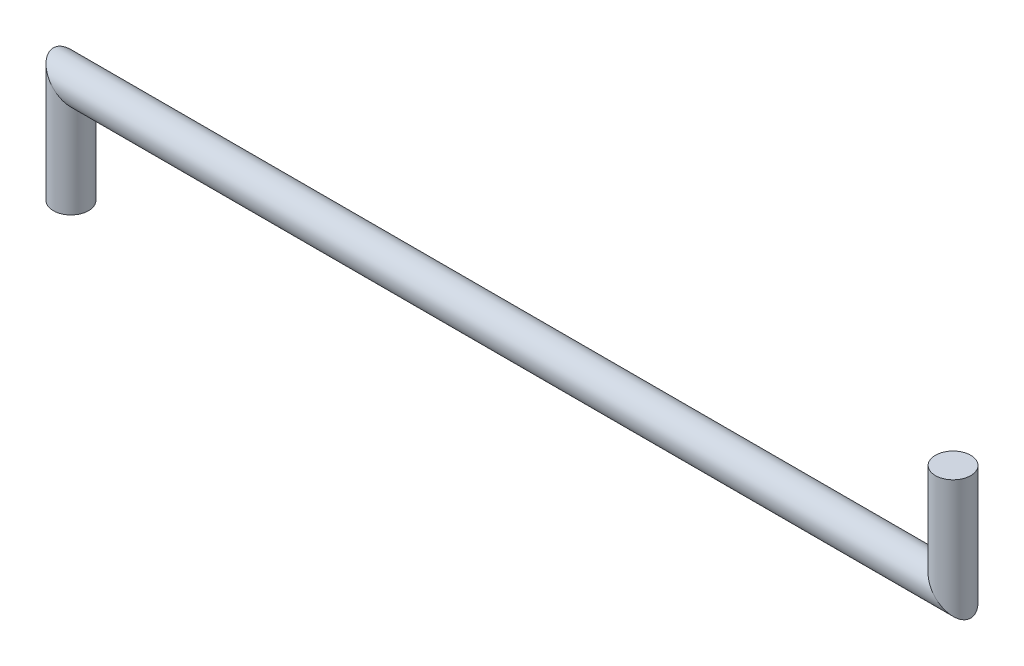
SolidWorks part; units mm, degrees
ref_plane "Alzado" through (0, 0, 0) normal (0, 0, 1) x (1, 0, 0)
ref_plane "Planta" through (0, 0, 0) normal (0, 1, 0) x (1, 0, 0)
ref_plane "Vista lateral" through (0, 0, 0) normal (1, 0, 0) x (0, 0, -1)
sketch "Croquis1" plane through (0, 0, 0) normal (0, 0, 1) x (1, 0, 0)
  line L0 (-62.0818, 4.9014) -> (-37.0818, 4.9014)
  line L1 (-62.0818, 4.9014) -> (-62.0818, 1.9014)
  line L2 (-37.0818, 4.9014) -> (-37.0818, 7.9014)
  dimension "D1" = 25
ref_plane "Plano1" through (0, 7.9014, 0) normal (0, 1, 0) x (1, 0, 0)
sketch "Croquis2" plane through (0, 7.9014, 0) normal (0, 1, 0) x (1, 0, 0)
  line L0 (-62.0818, 0) -> (-37.0818, 0) construction
  circle A0 centre (-37.0818, 0) radius 0.5
sweep "Barrer2" add profiles "Croquis2" path "Croquis1"
